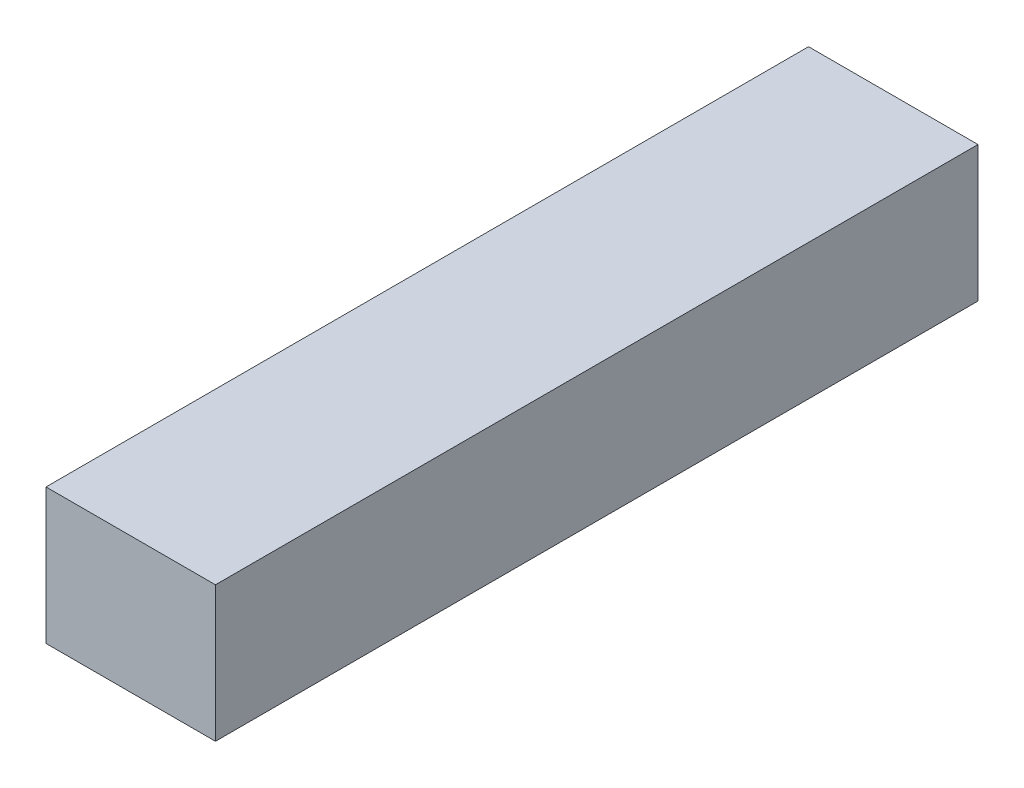
SolidWorks part; units mm, degrees
material "Ductile Iron"
ref_plane "Front Plane" through (0, 0, 0) normal (0, 0, 1) x (1, 0, 0)
ref_plane "Top Plane" through (0, 0, 0) normal (0, 1, 0) x (1, 0, 0)
ref_plane "Right Plane" through (0, 0, 0) normal (1, 0, 0) x (0, 0, -1)
sketch "Sketch1" plane through (0, 0, 0) normal (0, 0, 1) x (1, 0, 0)
  line L1 (0, 0) -> (10, 0)
  line L2 (0, 0) -> (0, -8)
  line L3 (0, -8) -> (10, -8)
  line L4 (10, 0) -> (10, -8)
  dimension "D1" = 8
  dimension "D2" = 10
extrude "Boss-Extrude1" add sketch "Sketch1" along normal blind 45
